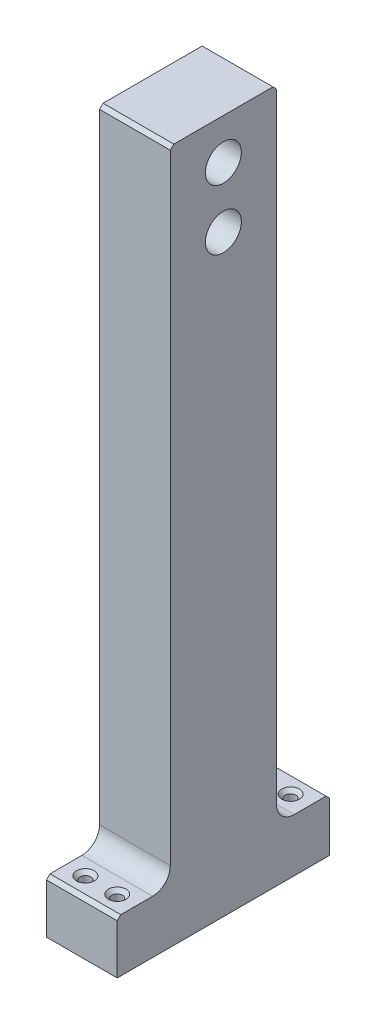
SolidWorks part; units mm, degrees
ref_plane "Front Plane" through (0, 0, 0) normal (0, 0, 1) x (1, 0, 0)
ref_plane "Top Plane" through (0, 0, 0) normal (0, 1, 0) x (1, 0, 0)
ref_plane "Right Plane" through (0, 0, 0) normal (1, 0, 0) x (0, 0, -1)
sketch "Sketch1" plane through (0, 0, 0) normal (1, 0, 0) x (0, 0, -1)
  line L0 (15, 196.075) -> (15, 15) construction
  line L1 (0, 0) -> (60, 0)
  line L2 (0, 0) -> (0, 15)
  line L3 (15, 196.075) -> (45, 196.075)
  line L4 (60, 0) -> (60, 15)
  line L5 (45, 196.075) -> (45, 15) construction
  line L6 (0, 15) -> (15, 15) construction
  line L7 (0, 15) -> (15, 15)
  line L8 (15, 15) -> (15, 196.075)
  line L9 (45, 196.075) -> (45, 15)
  line L10 (45, 15) -> (60, 15)
  line L11 (45, 15) -> (60, 15) construction
  line L12 (30, 196.075) -> (30, 21.1122) construction
  circle A0 centre (30, 184.575) radius 5.075
  circle A1 centre (30, 167.575) radius 5.075
  dimension "D1" = 10.15
  dimension "D2" = 10.15
  dimension "D3" = 15
  dimension "D4" = 15
  dimension "D5" = 15
  dimension "D6" = 11.5
  dimension "D7" = 17
  dimension "D8" = 181.075
extrude "Boss-Extrude1" add sketch "Sketch1" along normal blind 20
chamfer "Chamfer1" distance 1 angle 45 4 edges at (10, 15, 0) (10, 196.075, -15) (10, 15, -60) (10, 196.075, -45)
fillet "Fillet1" radius 5 2 edges at (10, 15, -45) (10, 15, -15)
sketch "Sketch2" plane through (0, 15, 0) normal (0, 1, 0) x (1, 0, 0)
  line L0 (0, 5.5) -> (20, 5.5) construction
  line L1 (0, 10) -> (0, 1) construction
  line L2 (20, 10) -> (20, 1) construction
  line L3 (0, 54.5) -> (20, 54.5) construction
  line L4 (0, 59) -> (0, 50) construction
  line L5 (20, 59) -> (20, 50) construction
  circle A0 centre (5.5, 54.5) radius 1.5
  circle A1 centre (14.5, 54.5) radius 1.5
  circle A2 centre (5.5, 5.5) radius 1.5
  circle A3 centre (14.5, 5.5) radius 1.5
  dimension "D1" = 3
  dimension "D2" = 3
  dimension "D5" = 3
  dimension "D6" = 3
  dimension "D3" = 9
  dimension "D4" = 5.5
extrude "Cut-Extrude1" cut sketch "Sketch2" against normal blind 15
chamfer "Chamfer2" distance 1 angle 45 4 edges at (5.5, 15, -53) (14.5, 15, -53) (5.5, 15, -4) (14.5, 15, -4)
